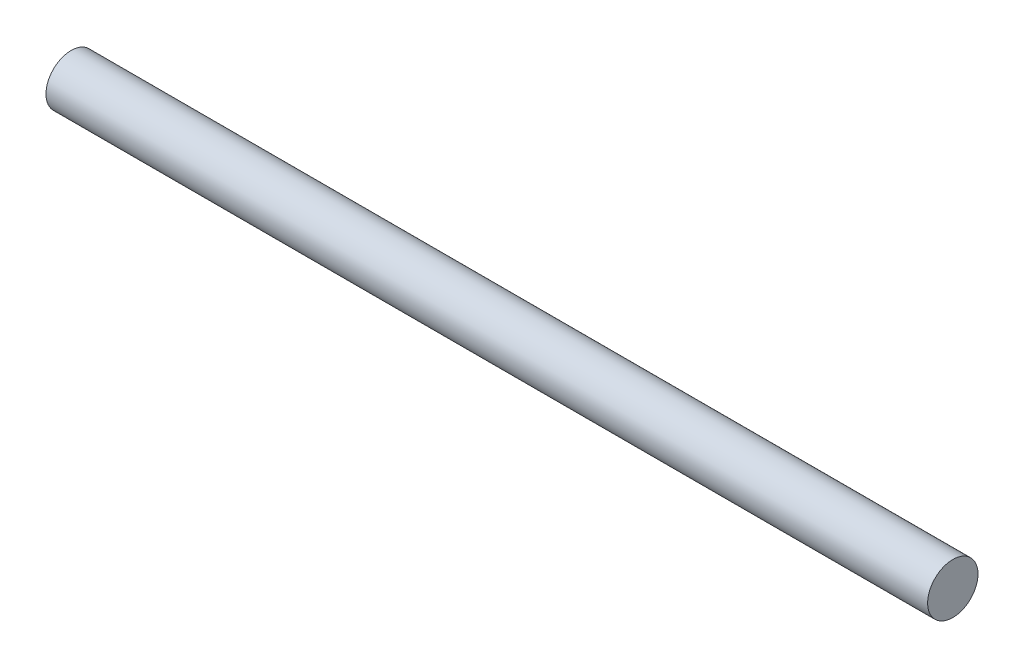
SolidWorks part; units mm, degrees
material "Plain Carbon Steel"
ref_plane "Front Plane" through (0, 0, 0) normal (0, 0, 1) x (1, 0, 0)
ref_plane "Top Plane" through (0, 0, 0) normal (0, 1, 0) x (1, 0, 0)
ref_plane "Right Plane" through (0, 0, 0) normal (1, 0, 0) x (0, 0, -1)
sketch "Sketch1" plane through (0, 0, 0) normal (0, 0, 1) x (1, 0, 0)
  line L0 (70, 0) -> (45.9678, 0) construction
  line L1 (0, 0) -> (70, 0)
  line L2 (0, 0) -> (0, 2)
  line L3 (0, 2) -> (70, 2)
  line L4 (70, 0) -> (70, 2)
  dimension "D1" = 2
  dimension "D2" = 70
revolve "Revolve1" add sketch "Sketch1" angle 360 about L0
